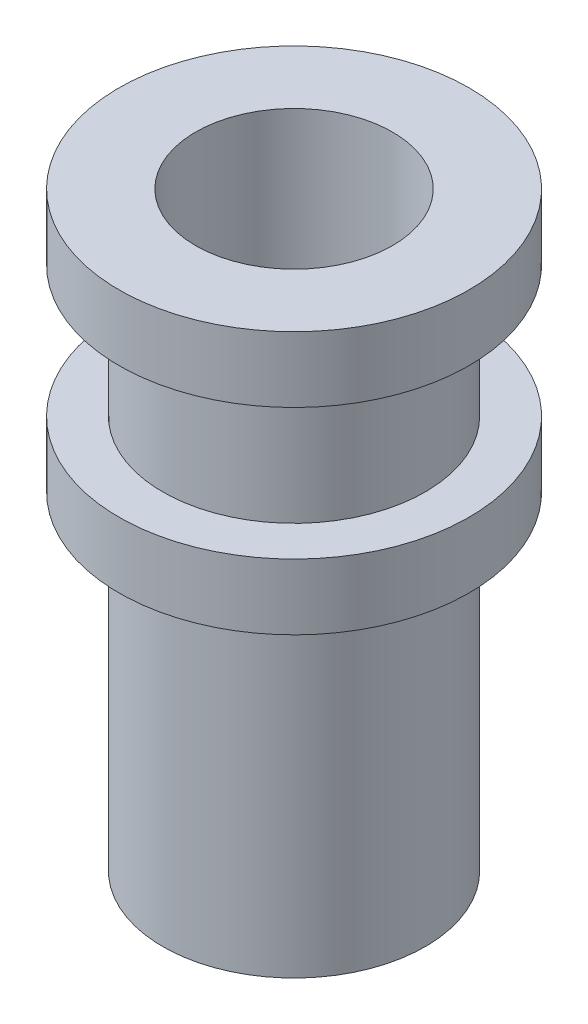
SolidWorks part; units mm, degrees
ref_plane "前基準面" through (0, 0, 0) normal (0, 0, 1) x (1, 0, 0)
ref_plane "上基準面" through (0, 0, 0) normal (0, 1, 0) x (1, 0, 0)
ref_plane "右基準面" through (0, 0, 0) normal (1, 0, 0) x (0, 0, -1)
sketch "草圖1" plane through (0, 0, 0) normal (0, 0, 1) x (1, 0, 0)
  line L0 (0, 0) -> (0, 14972.8656)
  line L1 (0, 14972.8656) -> (-8000, 14972.8656)
  line L2 (-8000, 14972.8656) -> (-8000, 11972.8656)
  line L3 (-8000, 11972.8656) -> (-6000, 11972.8656)
  line L4 (-6000, 11972.8656) -> (-6000, 5972.8656)
  line L5 (-6000, 5972.8656) -> (-8000, 5972.8656)
  line L6 (-8000, 5972.8656) -> (-8000, 2972.8656)
  line L7 (-8000, 2972.8656) -> (-6000, 2972.8656)
  line L8 (-6000, 2972.8656) -> (-6000, -12027.1344)
  line L9 (-6000, -12027.1344) -> (0, -12027.1344)
  line L10 (0, -12027.1344) -> (0, 0)
  dimension "D1" = 3000
  dimension "D2" = 6000
  dimension "D3" = 3000
  dimension "D4" = 6000
  dimension "D5" = 8000
  dimension "D6" = 8000
  dimension "D7" = 15000
revolve "旋轉1" add sketch "草圖1" angle 360 about L0
sketch "草圖2" plane through (0, -12027.1344, 0) normal (0, -1, 0) x (1, 0, 0)
  circle A0 centre (0, 0) radius 2250
  circle A1 centre (0, 0) radius 900
  dimension "D1" = 1800
  dimension "D2" = 4500
extrude "除料-伸長1" cut sketch "草圖2" along direction (0, 1, 0) on the side against the normal blind 5000
sketch "草圖3" plane through (0, -12027.1344, 0) normal (0, -1, 0) x (1, 0, 0)
  circle A0 centre (0, 0) radius 900
extrude "除料-伸長3" cut sketch "草圖3" against normal through all
sketch "草圖4" plane through (0, 14972.8656, 0) normal (0, 1, 0) x (1, 0, 0)
  circle A0 centre (0, 0) radius 4500
  dimension "D1" = 9000
extrude "除料-伸長4" cut sketch "草圖4" against normal blind 8000
chamfer "導角1" distance 3000 angle 45 1 edges at (0, 6972.8656, 900)
